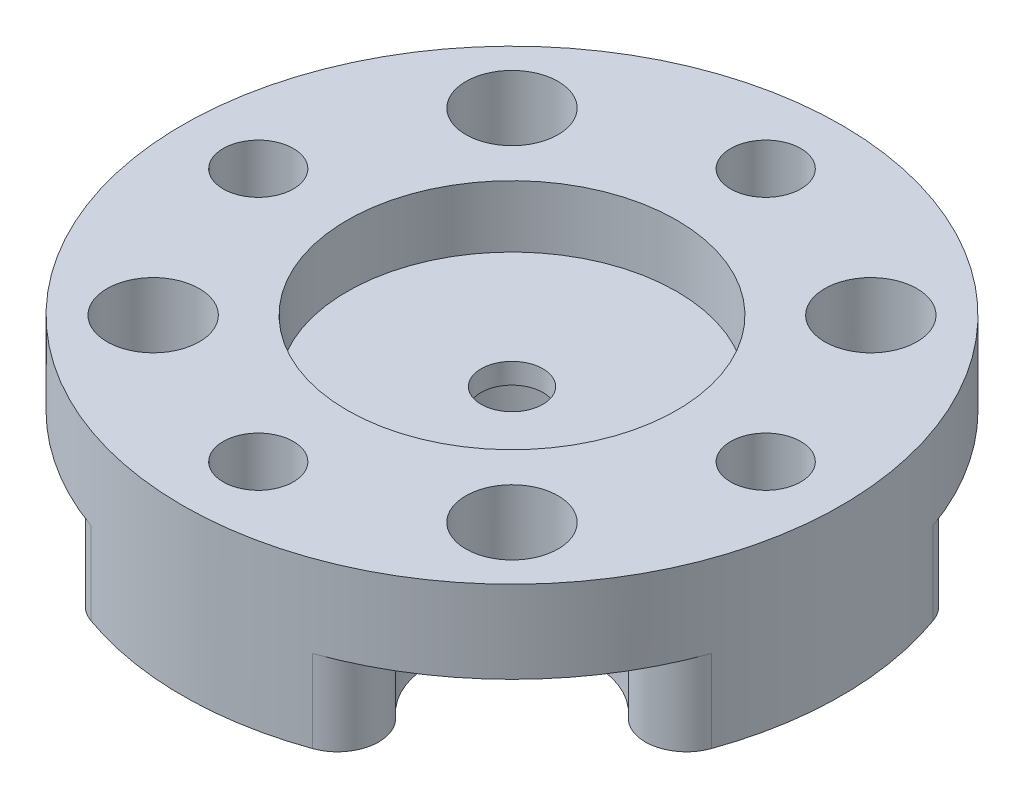
SolidWorks part; units mm, degrees
ref_plane "Front Plane" through (0, 0, 0) normal (0, 0, 1) x (1, 0, 0)
ref_plane "Top Plane" through (0, 0, 0) normal (0, 1, 0) x (1, 0, 0)
ref_plane "Right Plane" through (0, 0, 0) normal (1, 0, 0) x (0, 0, -1)
sketch "Sketch1" plane through (0, 0, 0) normal (0, 1, 0) x (1, 0, 0)
  circle A0 centre (0, 0) radius 12.7
  dimension "D1" = 25.4
extrude "Boss-Extrude1" add sketch "Sketch1" along normal blind 6.35
sketch "Sketch2" plane through (0, 6.35, 0) normal (0, 1, 0) x (1, 0, 0)
  circle A0 centre (0, 0) radius 6.35
  dimension "D1" = 12.7
extrude "Cut-Extrude1" cut sketch "Sketch2" against normal blind 2.3813
sketch "Sketch3" plane through (0, 0, 0) normal (0, -1, 0) x (1, 0, 0)
  circle A0 centre (0, 0) radius 3.1115
  dimension "D1" = 6.223
extrude "Cut-Extrude2" cut sketch "Sketch3" against normal blind 3.175
sketch "Sketch4" plane through (0, 3.9688, 0) normal (0, 1, 0) x (1, 0, 0)
  circle A0 centre (0, 0) radius 1.1906
  dimension "D1" = 2.3813
extrude "Cut-Extrude3" cut sketch "Sketch4" against normal through all
hole_wizard "#6-32 Tapped Hole1" positions "Sketch6" profile "Sketch5" tap size "#6-32" standard "ANSI Inch" end condition through all
sketch "Sketch6" plane through (0, 6.35, 0) normal (0, 1, 0) x (1, 0, 0)
  point P2 (-9.779, 0)
sketch "Sketch5" plane through (-9.779, 6.35, 0) normal (1, 0, 0) x (0, 0, 1)
  line L0 (0, 0) -> (0, 6.35)
  line L1 (0, 6.35) -> (1.3525, 6.35)
  line L2 (1.3525, 6.35) -> (1.3525, 0)
  line L5 (1.3525, 0) -> (0, 0)
  line L11 (0, -6.35) -> (0, 107.95) construction
  dimension "Thru Tap Drill Dia." = 2.7051
  dimension "Thru Tap Drill Depth" = 6.35
cosmetic thread "Hole Thread5" parameters "D2"=3.5052
sketch "Sketch7" plane through (0, 6.35, 0) normal (0, 1, 0) x (1, 0, 0)
  line L0 (0, 0) -> (6.9148, -6.9148) construction
  line L1 (0, 0) -> (0, -14.541) construction
  circle A0 centre (6.9148, -6.9148) radius 1.778
  dimension "D3" = 3.556
  dimension "D1" = 45
  dimension "D2" = 9.779
extrude "Cut-Extrude4" cut sketch "Sketch7" against normal through all
sketch "Sketch8" plane through (0, 0, 0) normal (0, -1, 0) x (1, 0, 0)
  circle A0 centre (6.9148, 6.9148) radius 3.175
  dimension "D1" = 6.35
extrude "Cut-Extrude5" cut sketch "Sketch8" against normal blind 3.175
pattern_circular "CirPattern2" count 4 over 360 about axis through (0, 0, 0) along (0, 1, 0) of "#6-32 Tapped Hole1", "Cut-Extrude4", "Cut-Extrude5"
fillet "Fillet1" radius 1.5875 8 edges at (7.9231, 1.5875, 9.9254) (9.9254, 1.5875, 7.9231) (9.9254, 1.5875, -7.9231) (7.9231, 1.5875, -9.9254) (-7.9231, 1.5875, -9.9254) (-9.9254, 1.5875, -7.9231) (-9.9254, 1.5875, 7.9231) (-7.9231, 1.5875, 9.9254)
